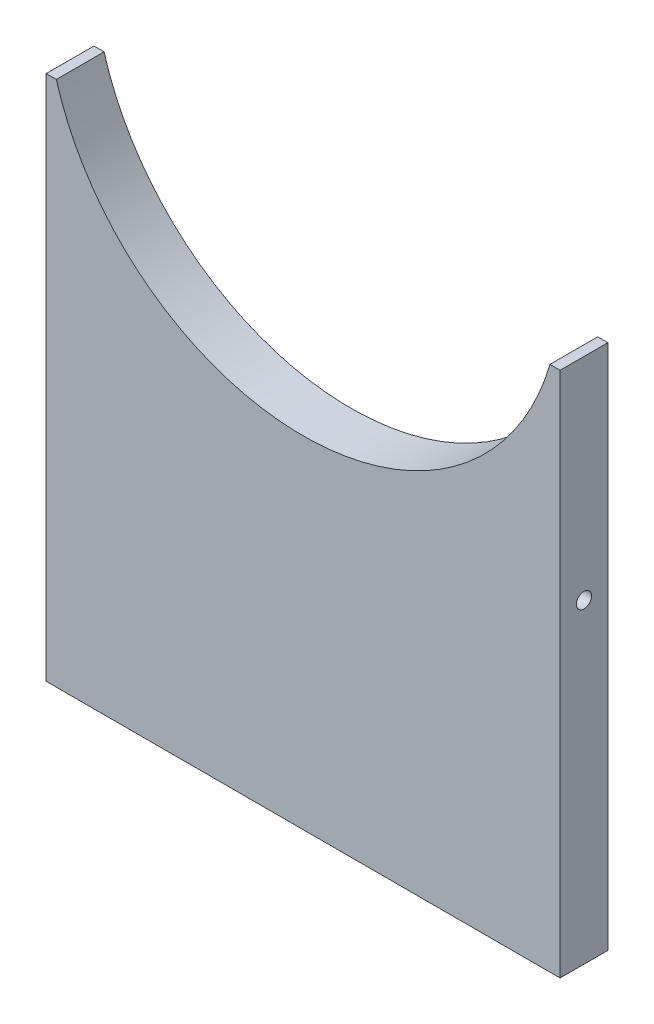
SolidWorks part; units mm, degrees
material "6061 Alloy"
ref_plane "Front Plane" through (0, 0, 0) normal (0, 0, 1) x (1, 0, 0)
ref_plane "Top Plane" through (0, 0, 0) normal (0, 1, 0) x (1, 0, 0)
ref_plane "Right Plane" through (0, 0, 0) normal (1, 0, 0) x (0, 0, -1)
sketch "Sketch1" plane through (0, 0, 0) normal (0, 0, 1) x (1, 0, 0)
  line L0 (0, 0) -> (0, 140)
  line L1 (0, 140) -> (2.7, 140)
  line L2 (0, 0) -> (136.7, 0)
  line L3 (136.7, 0) -> (136.7, 140)
  line L4 (136.7, 140) -> (134, 140)
  arc A2 (2.7, 140) -> (134, 140) centre (68.35, 159.0928) ccw
  dimension "D1" = 140
  dimension "D2" = 140
  dimension "D3" = 136.7
extrude "Boss-Extrude1" add sketch "Sketch1" along normal blind 12.7
sketch "Sketch2" plane through (136.7, 0, 0) normal (1, 0, 0) x (0, 0, -1)
  line L0 (-6.35, 140) -> (-6.35, 83.866) construction
  dimension "D1" = 56.134
hole_wizard "#10-32 Tapped Hole1" positions "3DSketch1" profile "Sketch3" tap size "#10-32" standard "Ansi Inch"
sketch3d "3DSketch1"
  point P0 (136.7, 83.866, 6.35)
sketch "Sketch3" plane through (136.7, 83.866, 6.35) normal (0, 1, 0) x (0, 0, -1)
  line L0 (0, 0) -> (0, 26.6133)
  line L1 (0, 26.6133) -> (2.0193, 25.4)
  line L2 (2.0193, 25.4) -> (2.0193, 0)
  line L5 (2.0193, 0) -> (0, 0)
  line L10 (0, 26.6133) -> (-2.0193, 25.4) construction
  line L11 (0, -6.35) -> (0, 107.95) construction
  dimension "Tap Drill Dia." = 4.0386
  dimension "Tap Drill Depth" = 25.4
  dimension "Drill Angle" = 118
sketch "Sketch4" plane through (0, 0, 0) normal (0, 0, 1) x (1, 0, 0)
  line L0 (68.35, 90.7228) -> (68.35, 0) construction
  line L1 (0, 0) -> (136.7, 0) construction
  line L2 (68.35, 90.7228) -> (68.35, 0) construction
sketch "Sketch5" plane through (0, 0, 12.7) normal (0, 0, 1) x (1, 0, 0)
  line L0 (68.35, 90.7228) -> (68.35, 0) construction
ref_plane "Plane1" through (68.35, 0, 0) normal (1, 0, 0) x (0, 0, -1)
mirror "Mirror3" about plane through (68.35, 0, 0) normal (1, 0, 0) of "#10-32 Tapped Hole1"
sketch "Sketch6" plane through (0, 0, 0) normal (0, -1, 0) x (1, 0, 0)
  line L0 (0, 6.35) -> (24.35, 6.35) construction
  line L1 (0, 12.7) -> (0, 0) construction
  line L2 (24.35, 6.35) -> (112.35, 6.35) construction
  line L6 (112.35, 6.35) -> (136.7, 6.35) construction
  line L7 (136.7, 12.7) -> (136.7, 0) construction
  dimension "D1" = 24.35
  dimension "D2" = 88
  dimension "D3" = 24.35
hole_wizard "#10-32 Tapped Hole2" positions "3DSketch2" profile "Sketch7" tap size "#10-32" standard "Ansi Inch"
sketch3d "3DSketch2"
  point P0 (112.35, 0, 6.35)
  point P3 (24.35, 0, 6.35)
sketch "Sketch7" plane through (112.35, 0, 6.35) normal (1, 0, 0) x (0, 0, -1)
  line L0 (0, 0) -> (0, 26.6133)
  line L1 (0, 26.6133) -> (2.0193, 25.4)
  line L2 (2.0193, 25.4) -> (2.0193, 0)
  line L5 (2.0193, 0) -> (0, 0)
  line L10 (0, 26.6133) -> (-2.0193, 25.4) construction
  line L11 (0, -6.35) -> (0, 107.95) construction
  dimension "Tap Drill Dia." = 4.0386
  dimension "Tap Drill Depth" = 25.4
  dimension "Drill Angle" = 118
